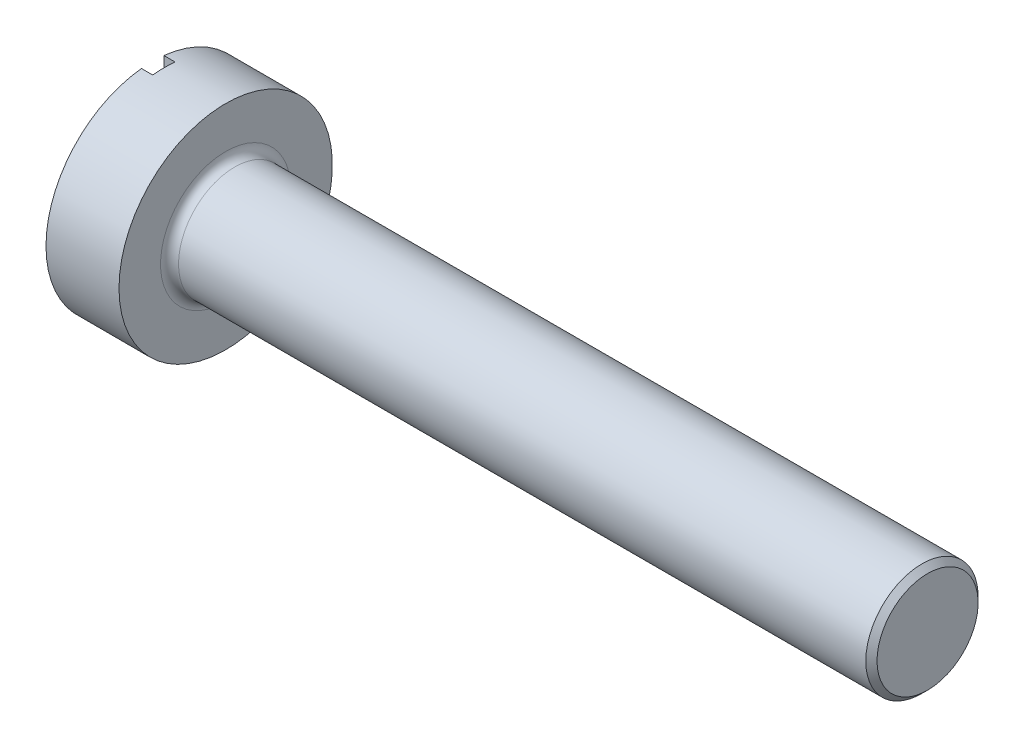
SolidWorks part; units mm, degrees
ref_plane "Front Plane" through (0, 0, 0) normal (0, 0, 1) x (1, 0, 0)
ref_plane "Top Plane" through (0, 0, 0) normal (0, 1, 0) x (1, 0, 0)
ref_plane "Right Plane" through (0, 0, 0) normal (1, 0, 0) x (0, 0, -1)
sketch "Sketch1" plane through (0, 0, 0) normal (0, 0, 1) x (1, 0, 0)
  line L0 (0, 0) -> (0, 1.9)
  line L1 (0, 1.9) -> (1.3, 1.9)
  line L2 (1.3, 1.9) -> (1.3, 0.4)
  line L3 (0, 0) -> (13.8, 0)
  line L4 (13.8, 0) -> (13.8, 1)
  line L5 (13.8, 1) -> (1.3, 1)
  dimension "D1" = 1.9
  dimension "D2" = 1.3
  dimension "D3" = 12.5
  dimension "D4" = 1
revolve "Revolve1" add sketch "Sketch1" angle 360 about L3
chamfer "Chamfer1" distance 0.1 angle 45 1 edges at (13.8, 0, 1)
fillet "Fillet1" radius 0.16 1 edges at (1.3, 0, 1)
sketch "Sketch2" plane through (0, 0, 0) normal (0, 1, 0) x (1, 0, 0)
  line L1 (0, 0) -> (0.2, 0)
  line L2 (0, 0) -> (0, 0.2)
  line L3 (0, 0.2) -> (0.2, 0.2)
  line L4 (0.2, 0) -> (0.2, 0.2)
  line L5 (0, 0) -> (0.2, 0)
  line L6 (0, 0) -> (0, -0.2)
  line L7 (0, -0.2) -> (0.2, -0.2)
  line L8 (0.2, 0) -> (0.2, -0.2)
extrude "Extrude1" cut sketch "Sketch2" against normal through all both and the other way through all contours L8 L1 L6 L7 | L1 L4 L3 L2
